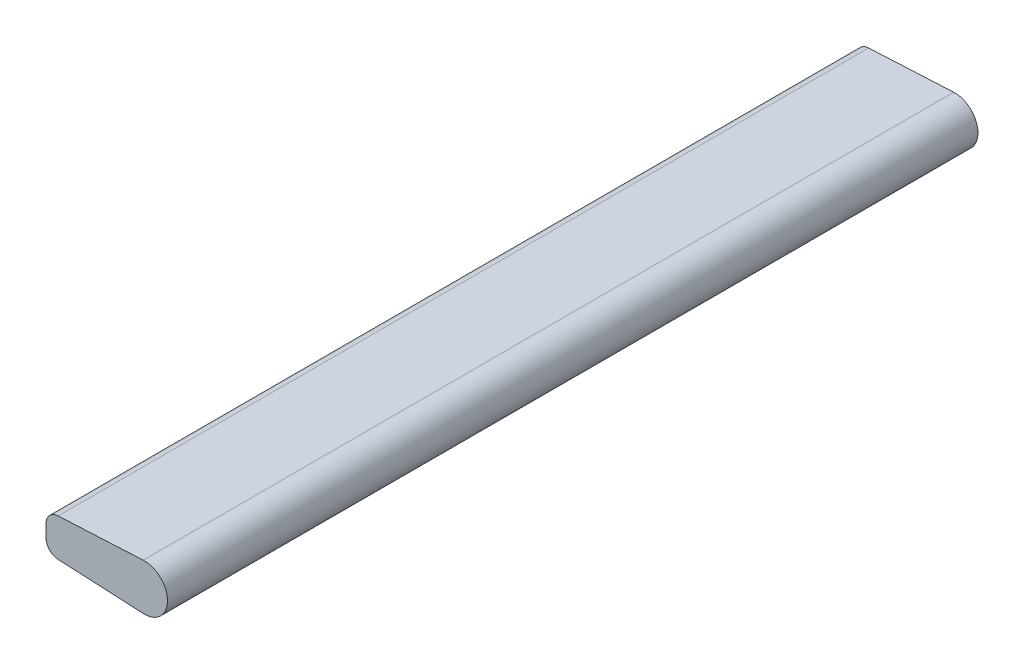
SolidWorks part; units mm, degrees
material "Wrought Copper"
ref_plane "Front Plane" through (0, 0, 0) normal (0, 0, 1) x (1, 0, 0)
ref_plane "Top Plane" through (0, 0, 0) normal (0, 1, 0) x (1, 0, 0)
ref_plane "Right Plane" through (0, 0, 0) normal (1, 0, 0) x (0, 0, -1)
sketch "Sketch1" plane through (0, 0, 0) normal (0, 0, 1) x (1, 0, 0)
  line L0 (0, 0) -> (-13.4964, 0) construction
  line L1 (-13.4964, -1.5) -> (-13.4964, 1.5)
  line L2 (-10.5, 4.65) -> (10.5, 5.7)
  line L3 (-10.5, -4.65) -> (10.5, -5.7)
  arc A0 (-13.4964, 1.5) -> (-10.5, 4.65) centre (-10.3425, 1.5) cw
  arc A1 (10.5, 5.7) -> (10.5, -5.7) centre (10.785, 0) cw
  arc A2 (-13.4964, -1.5) -> (-10.5, -4.65) centre (-10.3425, -1.5) ccw
  point P14 (0, 5.175)
  dimension "D1" = 21
  dimension "D2" = 9.3
  dimension "D3" = 11.4
  dimension "D4" = 3
extrude "Boss-Extrude1" add sketch "Sketch1" along normal mid plane 200
